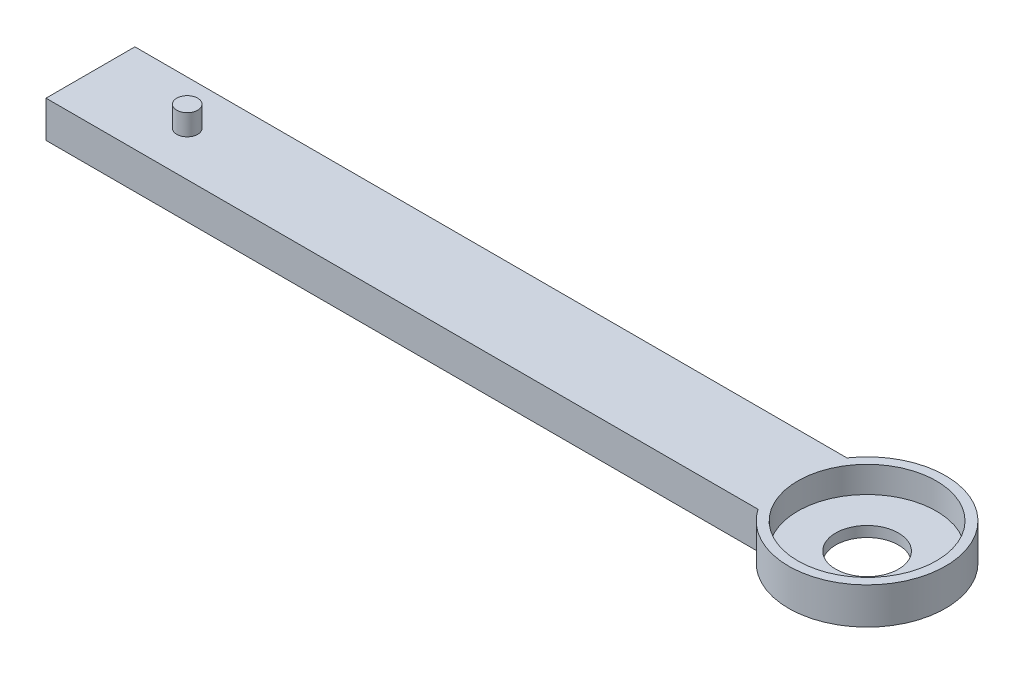
SolidWorks part; units mm, degrees
ref_plane "正面" through (0, 0, 0) normal (0, 0, 1) x (1, 0, 0)
ref_plane "平面" through (0, 0, 0) normal (0, 1, 0) x (1, 0, 0)
ref_plane "右側面" through (0, 0, 0) normal (1, 0, 0) x (0, 0, -1)
sketch "ｽｹｯﾁ3" plane through (0, 0, 0) normal (0, 0, 1) x (1, 0, 0)
  line L1 (0, 0) -> (148.5, 0)
  line L2 (0, 0) -> (0, -7)
  line L3 (0, -7) -> (148.5, -7)
  line L4 (148.5, 0) -> (148.5, -7)
  dimension "D1" = 7
  dimension "D2" = 148.5
extrude "ﾎﾞｽ - 押し出し1" add sketch "ｽｹｯﾁ3" along normal blind 17
sketch "ｽｹｯﾁ4" plane through (0, 0, 0) normal (0, 1, 0) x (1, 0, 0)
  line L0 (0, 0) -> (0, -8.5) construction
  line L1 (0, -17) -> (0, 0) construction
  line L2 (0, -8.5) -> (148.5, -8.5) construction
  line L3 (148.5, -17) -> (148.5, 0) construction
  circle A0 centre (148.5, -8.5) radius 13
  circle A1 centre (148.5, -8.5) radius 15
  dimension "D1" = 26
  dimension "D2" = 30
extrude "ｶｯﾄ - 押し出し3" cut sketch "ｽｹｯﾁ4" against normal through all contours A1
sketch "ｽｹｯﾁ6" plane through (0, 0, 0) normal (0, 1, 0) x (1, 0, 0)
  line L0 (0, 0) -> (0, -8.5) construction
  line L1 (0, -17) -> (0, 0) construction
  line L2 (0, -8.5) -> (148.5, -8.5) construction
  circle A0 centre (148.5, -8.5) radius 15
  dimension "D1" = 148.5
extrude "ﾎﾞｽ - 押し出し2" add sketch "ｽｹｯﾁ6" against normal blind 7
sketch "ｽｹｯﾁ7" plane through (0, 0, 0) normal (0, 1, 0) x (1, 0, 0)
  circle A0 centre (148.5, -8.5) radius 13.25
  dimension "D1" = 26.5
extrude "ｶｯﾄ - 押し出し4" cut sketch "ｽｹｯﾁ7" against normal blind 5
sketch "ｽｹｯﾁ8" plane through (0, -5, 0) normal (0, 1, 0) x (1, 0, 0)
  circle A0 centre (148.5, -8.5) radius 6
  dimension "D1" = 12
extrude "ｶｯﾄ - 押し出し5" cut sketch "ｽｹｯﾁ8" against normal through all
sketch "ｽｹｯﾁ9" plane through (0, 0, 0) normal (0, 1, 0) x (1, 0, 0)
  line L0 (0, -17) -> (18.5, -17) construction
  line L1 (136.1408, -17) -> (0, -17) construction
  line L2 (18.5, -17) -> (18.5, -8.5) construction
  line L3 (18.5, -8.5) -> (148.5, -8.5) construction
  circle A0 centre (18.5, -8.5) radius 2
  dimension "D3" = 4
  dimension "D1" = 130
  dimension "D2" = 8.5
extrude "ﾎﾞｽ - 押し出し3" add sketch "ｽｹｯﾁ9" along normal blind 4
sketch "ｽｹｯﾁ12" plane through (0, -7, 0) normal (0, -1, 0) x (1, 0, 0)
  text T0 "B2"
extrude "ｶｯﾄ - 押し出し7" cut sketch "ｽｹｯﾁ12" against normal blind 1
